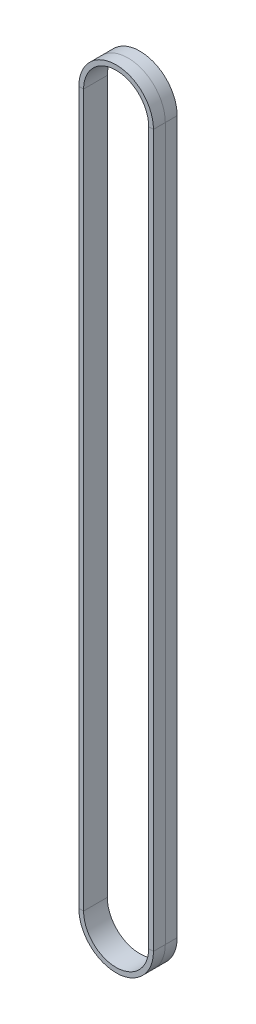
SolidWorks part; units mm, degrees
ref_plane "前视基准面" through (0, 0, 0) normal (0, 0, 1) x (1, 0, 0)
ref_plane "上视基准面" through (0, 0, 0) normal (0, 1, 0) x (1, 0, 0)
ref_plane "右视基准面" through (0, 0, 0) normal (1, 0, 0) x (0, 0, -1)
sketch "草图2" plane through (0, 0, 0) normal (0, 0, 1) x (1, 0, 0)
  line L0 (0, 0) -> (1, 0) construction
  line L1 (0, 0) -> (0, 1) construction
  line L2 (-43.6095, 0) -> (-43.6095, 300)
  line L3 (-15.7195, 300) -> (-15.7195, 0)
  arc A0 (-15.7195, 0) -> (-43.6095, 0) centre (-29.6645, 0) cw
  arc A1 (-43.6095, 300) -> (-15.7195, 300) centre (-29.6645, 300) cw
sketch "草图4" plane through (0, 0, 0) normal (0, 1, 0) x (1, 0, 0)
  line L0 (-13.945, 0) -> (-13.945, 5)
  line L1 (-43.6095, 0) -> (-15.7195, 0) construction
  line L2 (-13.945, 0) -> (-13.945, -5)
  line L3 (-13.945, 5) -> (-15.945, 5)
  line L4 (-15.945, 5) -> (-15.945, -5)
  line L5 (-15.945, -5) -> (-13.945, -5)
  dimension "D1" = 5
  dimension "D2" = 5
  dimension "D3" = 2
sweep "扫描1" add profiles "草图4" path "草图2"
